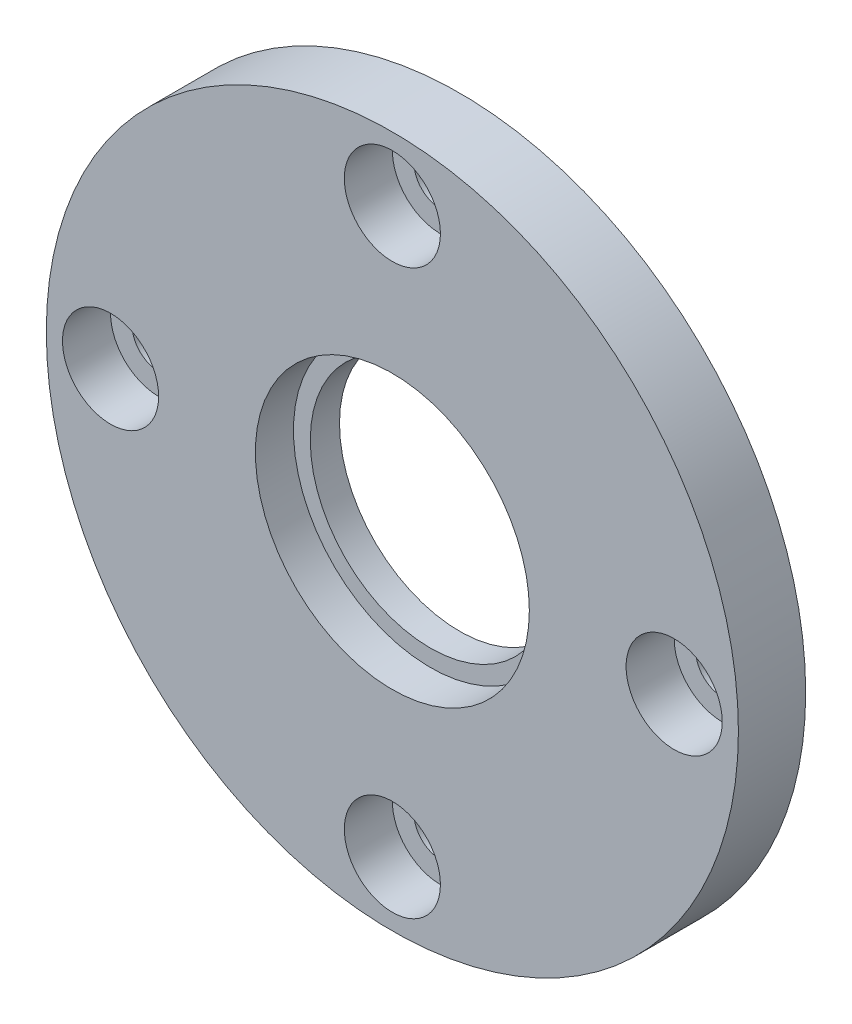
SolidWorks part; units mm, degrees
ref_plane "Front Plane" through (0, 0, 0) normal (0, 0, 1) x (1, 0, 0)
ref_plane "Top Plane" through (0, 0, 0) normal (0, 1, 0) x (1, 0, 0)
ref_plane "Right Plane" through (0, 0, 0) normal (1, 0, 0) x (0, 0, -1)
sketch "Sketch1" plane through (0, 0, 0) normal (1, 0, 0) x (0, 0, -1)
  line L0 (-116.9, -9.5) -> (-149, -9.5)
  line L5 (-1000, 0) -> (49000, 0)
  line L6 (0, -9.5) -> (0, 9.5)
  line L13 (0, 9.5) -> (-55.3, 9.5)
  line L26 (-55.3, 9.5) -> (-55.3, 14)
  line L27 (-55.3, 14) -> (-116.9, 14)
  line L32 (-116.9, 14) -> (-116.9, 9.5)
  line L34 (-165, 7) -> (-165, -7)
  line L36 (-116.9, -9.5) -> (-116.9, -14)
  line L37 (-116.9, -14) -> (-55.3, -14)
  line L38 (-55.3, -14) -> (-55.3, -9.5)
  line L39 (0, -9.5) -> (-55.3, -9.5)
  line L40 (-20.873, 36) -> (-13.873, 36)
  line L41 (-133.5, 22.6312) -> (-116.9, 22.6312)
  line L42 (-133.5, 22.6312) -> (-133.5, -22.6312)
  line L43 (-133.5, -22.6312) -> (-116.9, -22.6312)
  line L44 (-116.9, 22.6312) -> (-116.9, -22.6312)
  line L45 (-133.5, 22.6312) -> (-116.9, -22.6312) construction
  line L46 (-133.5, -22.6312) -> (-116.9, 22.6312) construction
  line L47 (-38.7, 22.6312) -> (-55.3, 22.6312)
  line L48 (-38.7, 22.6312) -> (-38.7, -22.6312)
  line L49 (-38.7, -22.6312) -> (-55.3, -22.6312)
  line L50 (-55.3, 22.6312) -> (-55.3, -22.6312)
  line L51 (-38.7, 22.6312) -> (-55.3, -22.6312) construction
  line L52 (-38.7, -22.6312) -> (-55.3, 22.6312) construction
  line L59 (-13.873, 36) -> (-13.873, -36)
  line L60 (-13.873, -36) -> (-20.873, -36)
  line L61 (-20.873, -22.6312) -> (-25.873, -22.6312)
  line L62 (-25.873, -22.6312) -> (-25.873, -12.6312)
  line L63 (-25.873, -12.6312) -> (-20.873, -12.6312)
  line L64 (-20.873, -12.6312) -> (-20.873, 12.6312)
  line L65 (-20.873, 12.6312) -> (-25.873, 12.6312)
  line L66 (-25.873, 12.6312) -> (-25.873, 22.6312)
  line L67 (-25.873, 22.6312) -> (-20.873, 22.6312)
  line L68 (-20.873, 22.6312) -> (-20.873, 36)
  line L69 (-20.873, -22.6312) -> (-20.873, -36)
  line L71 (-135.659, 36) -> (-21.873, 36)
  line L72 (-135.659, 36) -> (-135.659, -36)
  line L73 (-135.659, -36) -> (-21.873, -36)
  line L74 (-21.873, 36) -> (-21.873, -36)
  line L75 (-135.659, 36) -> (-21.873, -36) construction
  line L76 (-135.659, -36) -> (-21.873, 36) construction
  line L77 (-149, -9.5) -> (-149, -7)
  line L78 (-149, -7) -> (-165, -7)
  line L79 (-116.9, 9.5) -> (-149, 9.5)
  line L80 (-149, 7) -> (-165, 7)
  line L81 (-149, 9.5) -> (-149, 7)
  line L82 (-132.95, 9.5) -> (-132.95, -9.5) construction
  line L83 (-27.65, 9.5) -> (-27.65, -9.5) construction
  line L96 (-135.659, 36) -> (-142.659, 36)
  line L98 (-135.659, -36) -> (-142.659, -36)
  line L99 (-142.659, 36) -> (-142.659, -36)
  line L110 (-135.659, 36) -> (-135.659, -36)
  point P3 (0, 0)
  point P18 (-125.2, 0)
  point P24 (-47, 0)
  point P29 (-78.766, 0)
  point P48 (-13.873, 29.3156)
  point P70 (-142.659, 29.3156)
revolve "Main_body" add sketch "Sketch1" angle 360 about L5
sketch "Sketch2" plane through (0, 0, 135.659) normal (0, 0, -1) x (-1, 0, 0)
  circle A1 centre (0, 0) radius 12.5
  dimension "D1" = 25
extrude "Shaft_thru" cut sketch "Sketch2" against normal through all
hole_wizard "CBORE for M5 SHCS1" positions "Sketch3" profile "Sketch4" counterbore size "M5" standard "ANSI Metric" end condition through all
sketch "Sketch3" plane through (0, 0, 142.659) normal (0, 0, 1) x (1, 0, 0)
  point P0 (0, 29.3156)
sketch "Sketch4" plane through (0, 29.3156, 142.659) normal (1, 0, 0) x (0, -1, 0)
  line L0 (0, 0) -> (0, 7)
  line L1 (0, 7) -> (2.75, 7)
  line L3 (2.75, 7) -> (2.75, 5)
  line L4 (2.75, 5) -> (5, 5)
  line L5 (5, 5) -> (5, 0)
  line L7 (5, 0) -> (0, 0)
  line L11 (0, -6.35) -> (0, 107.95) construction
  dimension "Thru Hole Dia." = 5.5
  dimension "Thru Hole Depth" = 7
  dimension "C'Bore Dia." = 10
  dimension "C'Bore Depth" = 5
pattern_circular "CirPattern1" count 4 over 360 about axis through (0, 0, 0) along (0, 0, 1) of "CBORE for M5 SHCS1"
sketch "Sketch5" plane through (0, 0, 142.659) normal (0, 0, 1) x (1, 0, 0)
  circle A0 centre (0, 0) radius 14.25
  dimension "D1" = 28.5
extrude "seal_seat" cut sketch "Sketch5" against normal blind 3.9624
